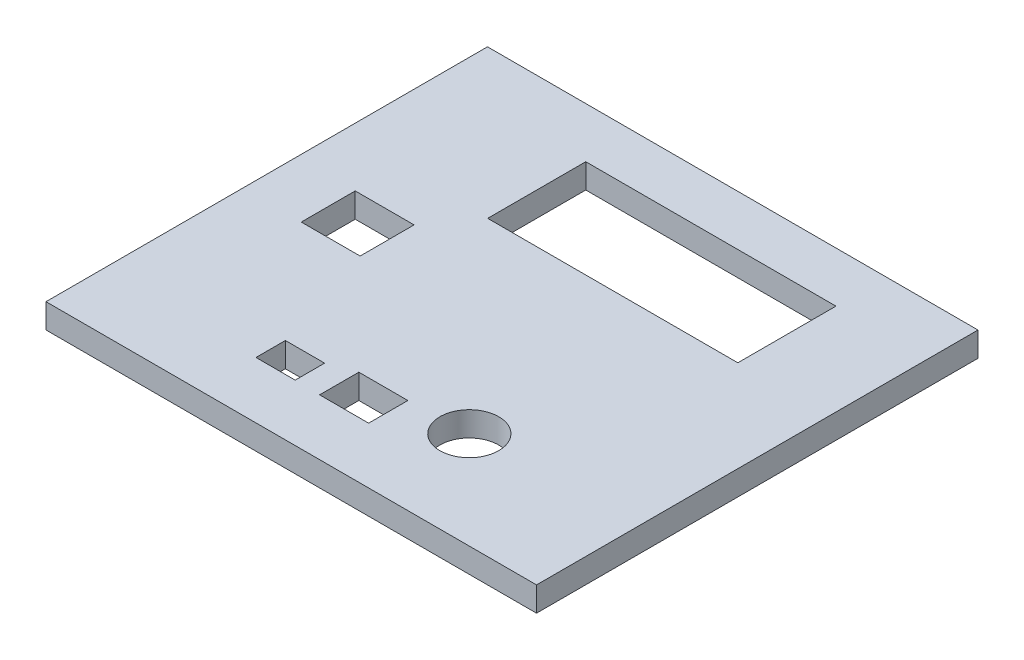
SolidWorks part; units mm, degrees
ref_plane "Front Plane" through (0, 0, 0) normal (0, 0, 1) x (1, 0, 0)
ref_plane "Top Plane" through (0, 0, 0) normal (0, 1, 0) x (1, 0, 0)
ref_plane "Right Plane" through (0, 0, 0) normal (1, 0, 0) x (0, 0, -1)
sketch "Sketch1" plane through (0, 0, 0) normal (0, 1, 0) x (1, 0, 0)
  line L1 (-50, -45) -> (50, -45)
  line L2 (-50, -45) -> (-50, 45)
  line L3 (-50, 45) -> (50, 45)
  line L4 (50, -45) -> (50, 45)
  line L5 (-50, -45) -> (50, 45) construction
  line L6 (-50, 45) -> (50, -45) construction
  point P0 (0, 0)
  dimension "D1" = 100
  dimension "D2" = 90
extrude "Boss-Extrude2" add sketch "Sketch1" along normal blind 5 contours L3 L4 L1 L2
sketch "Sketch2" plane through (0, 0, 0) normal (0, 1, 0) x (1, 0, 0)
  line L0 (-42, 37) -> (42, 37)
  line L2 (-42, -37) -> (42, -37)
  line L3 (-38.0374, -4.9233) -> (-26.0374, -4.9233)
  line L4 (-42, 37) -> (-42, -37)
  line L5 (-38.0374, -4.9233) -> (-38.0374, 6.0767)
  line L6 (42, 37) -> (42, -37)
  line L7 (-38.0374, 6.0767) -> (-26.0374, 6.0767)
  line L8 (-26.0374, -4.9233) -> (-26.0374, 6.0767)
  line L9 (-42, -37) -> (42, -37)
  line L10 (-42, -37) -> (-42, 37)
  line L11 (-42, 37) -> (42, 37)
  line L13 (-19.6931, 14.7327) -> (31.3069, 14.7327)
  line L14 (-19.6931, 14.7327) -> (-19.6931, 34.7327)
  line L15 (-19.6931, 34.7327) -> (31.3069, 34.7327)
  line L16 (31.3069, 14.7327) -> (31.3069, 34.7327)
  line L17 (-19.6931, 14.7327) -> (31.3069, 34.7327) construction
  line L18 (-19.6931, 34.7327) -> (31.3069, 14.7327) construction
  line L19 (-38.0374, -4.9233) -> (-26.0374, 6.0767) construction
  line L20 (-38.0374, 6.0767) -> (-26.0374, -4.9233) construction
  line L21 (-5.6651, -33.5606) -> (4.3349, -33.5606)
  line L22 (-5.6651, -33.5606) -> (-5.6651, -25.5606)
  line L23 (-5.6651, -25.5606) -> (4.3349, -25.5606)
  line L24 (4.3349, -33.5606) -> (4.3349, -25.5606)
  line L25 (-5.6651, -33.5606) -> (4.3349, -25.5606) construction
  line L26 (-5.6651, -25.5606) -> (4.3349, -33.5606) construction
  line L27 (-18.7489, -33.449) -> (-10.7489, -33.449)
  line L28 (-18.7489, -33.449) -> (-18.7489, -27.449)
  line L29 (-18.7489, -27.449) -> (-10.7489, -27.449)
  line L30 (-10.7489, -33.449) -> (-10.7489, -27.449)
  line L31 (-18.7489, -33.449) -> (-10.7489, -27.449) construction
  line L32 (-18.7489, -27.449) -> (-10.7489, -33.449) construction
  circle A3 centre (16.4559, -25.1559) radius 6
  point P0 (5.8069, 24.7327)
  point P5 (-32.0374, 0.5767)
  point P12 (-0.6651, -29.5606)
  point P16 (0, 0)
  point P23 (-14.7489, -30.449)
extrude "Cut-Extrude2" cut sketch "Sketch2" along normal through all contours L15 L16 L13 L14 | L7 L8 L3 L5 | L23 L24 L21 L22 | A3 | L27 L30 L29 L28
